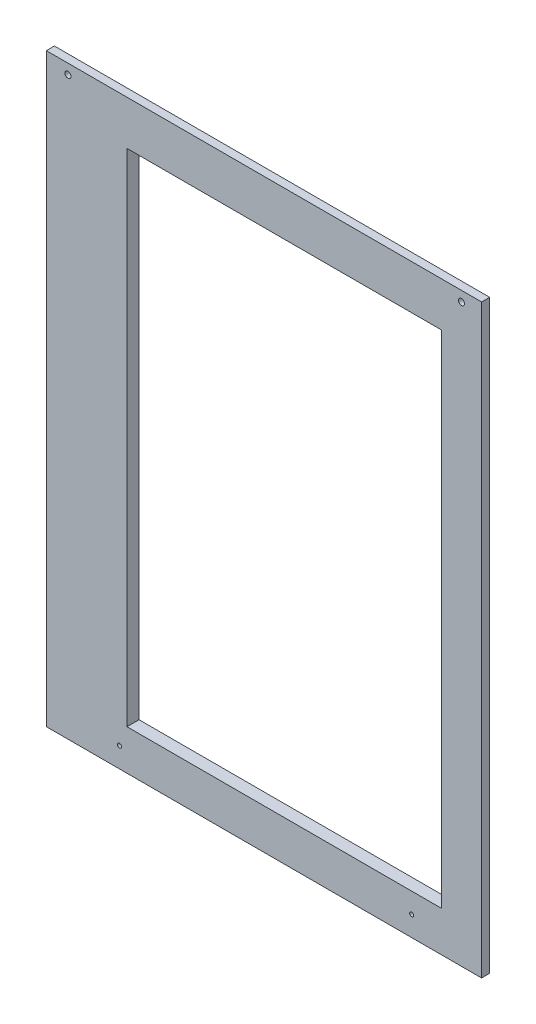
SolidWorks part; units mm, degrees
ref_plane "Plan de face" through (0, 0, 0) normal (0, 0, 1) x (1, 0, 0)
ref_plane "Plan de dessus" through (0, 0, 0) normal (0, 1, 0) x (1, 0, 0)
ref_plane "Plan de droite" through (0, 0, 0) normal (1, 0, 0) x (0, 0, -1)
sketch "Esquisse1" plane through (0, 0, 0) normal (0, 0, 1) x (1, 0, 0)
  line L9 (18.3499, 694.8961) -> (224.3499, 694.8961)
  line L10 (18.3499, 694.8961) -> (18.3499, 416.3427)
  line L12 (18.3499, 416.3427) -> (224.3499, 416.3427)
  line L14 (224.3499, 694.8961) -> (224.3499, 416.3427)
  dimension "D1" = 206
  dimension "D2" = 278.5534
extrude "Boss.-Extru.1" add sketch "Esquisse1" along normal blind 4
sketch "Esquisse2" plane through (0, 0, 4) normal (0, 0, 1) x (1, 0, 0)
  line L0 (224.3499, 694.8961) -> (18.3499, 694.8961) construction
  line L1 (13.3499, 701.8961) -> (229.3499, 701.8961)
  line L2 (13.3499, 701.8961) -> (13.3499, 411.3427)
  line L3 (13.3499, 411.3427) -> (229.3499, 411.3427)
  line L4 (229.3499, 701.8961) -> (229.3499, 411.3427)
  line L5 (18.3499, 694.8961) -> (18.3499, 416.3427) construction
  line L6 (18.3499, 416.3427) -> (224.3499, 416.3427) construction
  line L7 (224.3499, 416.3427) -> (224.3499, 694.8961) construction
  dimension "D1" = 7
  dimension "D2" = 5
  dimension "D3" = 5
  dimension "D4" = 5
extrude "Boss.-Extru.2" add sketch "Esquisse2" along normal blind 4
sketch "Esquisse3" plane through (0, 0, 0) normal (0, 0, -1) x (-1, 0, 0)
  line L0 (-224.3499, 694.8961) -> (-18.3499, 694.8961) construction
  line L1 (-209.3499, 679.8961) -> (-53.3499, 679.8961)
  line L2 (-209.3499, 679.8961) -> (-209.3499, 431.3427)
  line L3 (-209.3499, 431.3427) -> (-53.3499, 431.3427)
  line L4 (-53.3499, 679.8961) -> (-53.3499, 431.3427)
  line L5 (-18.3499, 694.8961) -> (-18.3499, 416.3427) construction
  line L6 (-18.3499, 416.3427) -> (-224.3499, 416.3427) construction
  line L7 (-224.3499, 416.3427) -> (-224.3499, 694.8961) construction
  dimension "D1" = 15
  dimension "D2" = 35
  dimension "D3" = 15
  dimension "D4" = 15
extrude "Enlèv. mat.-Extru.1" cut sketch "Esquisse3" against normal blind 8
sketch "Esquisse4" plane through (0, 0, 0) normal (0, 0, -1) x (-1, 0, 0)
  line L0 (-209.3499, 679.8961) -> (-209.3499, 431.3427) construction
  line L1 (-212.2286, 684.8961) -> (-50.4712, 684.8961)
  line L2 (-214.3499, 682.7748) -> (-214.3499, 428.4182)
  line L3 (-211.5832, 426.3427) -> (-51.1167, 426.3427)
  line L4 (-48.3499, 682.7748) -> (-48.3499, 428.4182)
  line L5 (-53.3499, 679.8961) -> (-209.3499, 679.8961) construction
  line L6 (-53.3499, 431.3427) -> (-53.3499, 679.8961) construction
  line L7 (-209.3499, 431.3427) -> (-53.3499, 431.3427) construction
  line L8 (-131.3499, 684.8961) -> (-131.3499, 396.3427) construction
  line L9 (-211.5832, 426.3427) -> (-212.2286, 426.3427)
  line L10 (-51.1167, 426.3427) -> (-50.4712, 426.3427)
  arc A0 (-214.3499, 428.4182) -> (-212.2286, 426.3427) centre (-213.136, 427.5371) ccw
  arc A1 (-50.4712, 426.3427) -> (-48.3499, 428.4182) centre (-49.5638, 427.5371) ccw
  arc A2 (-48.3499, 682.7748) -> (-50.4712, 684.8961) centre (-49.4106, 683.8354) ccw
  arc A3 (-212.2286, 684.8961) -> (-214.3499, 682.7748) centre (-213.2892, 683.8354) ccw
  dimension "D1" = 5
  dimension "D2" = 5
  dimension "D3" = 5
  dimension "D4" = 5
extrude "Enlèv. mat.-Extru.2" cut sketch "Esquisse4" against normal blind 2
sketch "Esquisse5" plane through (0, 0, 4) normal (0, 0, -1) x (-1, 0, 0)
  line L1 (-229.3499, 696.8961) -> (-14.0674, 696.8961) construction
  line L2 (-229.3499, 411.3427) -> (-229.3499, 701.8961) construction
  line L3 (-229.3499, 701.8961) -> (-13.3499, 701.8961) construction
  line L4 (-121.7087, 696.8961) -> (-121.7087, 705.9284) construction
  circle A0 centre (-219.3499, 696.8961) radius 1.5
  circle A1 centre (-24.0674, 696.8961) radius 1.5
  dimension "D2" = 10
  dimension "D1" = 5
extrude "Enlèv. mat.-Extru.3" cut sketch "Esquisse5" against normal blind 4
sketch "Esquisse6" plane through (0, 0, 0) normal (0, 0, -1) x (-1, 0, 0)
  circle A0 centre (-24.0674, 696.8961) radius 3
  circle A1 centre (-219.3499, 696.8961) radius 3
extrude "Enlèv. mat.-Extru.4" cut sketch "Esquisse6" against normal blind 4
sketch "Esquisse7" plane through (0, 0, 8) normal (0, 0, 1) x (1, 0, 0)
  line L0 (77.163, 425.3427) -> (22.163, 417.3427) construction
  line L1 (222.163, 425.3427) -> (167.163, 417.3427) construction
  circle A0 centre (49.663, 421.3427) radius 1
  circle A1 centre (194.663, 421.3427) radius 1
extrude "Enlèv. mat.-Extru.5" cut sketch "Esquisse7" against normal through all
